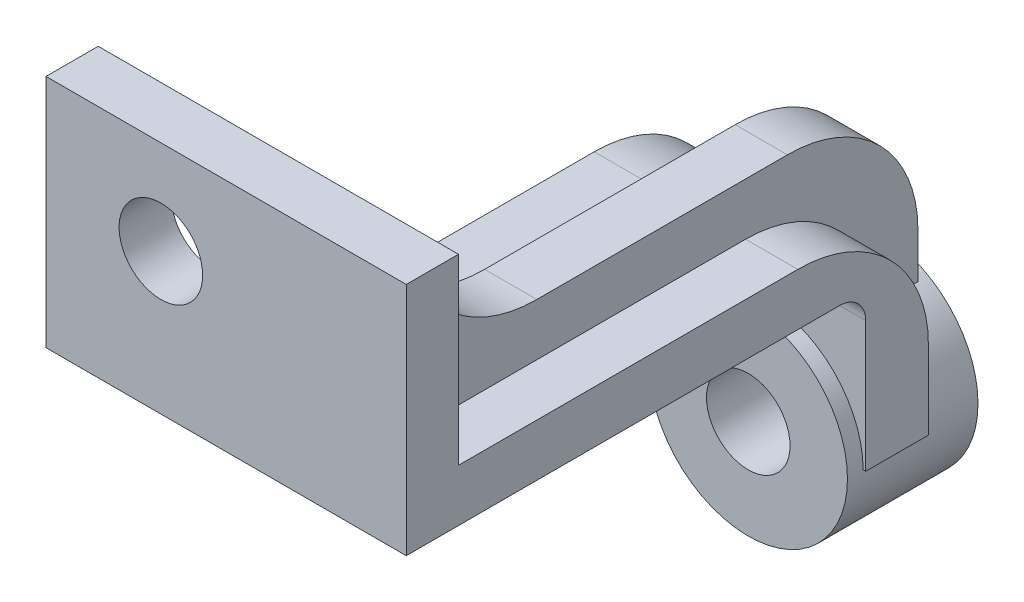
SolidWorks part; units mm, degrees
ref_plane "Ön Düzlem" through (0, 0, 0) normal (0, 0, 1) x (1, 0, 0)
ref_plane "Üst Düzlem" through (0, 0, 0) normal (0, 1, 0) x (1, 0, 0)
ref_plane "Sağ Düzlem" through (0, 0, 0) normal (1, 0, 0) x (0, 0, -1)
sketch "Çizim1" plane through (0, 0, 0) normal (0, 0, 1) x (1, 0, 0)
  line L1 (34.5, -22.5) -> (-34.5, -22.5)
  line L2 (34.5, -22.5) -> (34.5, 22.5)
  line L3 (34.5, 22.5) -> (-34.5, 22.5)
  line L4 (-34.5, -22.5) -> (-34.5, 22.5)
  line L5 (34.5, -22.5) -> (-34.5, 22.5) construction
  line L6 (34.5, 22.5) -> (-34.5, -22.5) construction
  circle A0 centre (-12.5, 4.5) radius 8
  point P0 (0, 0)
  point P8 (0, 0)
  point P10 (-8.0343, 5.2398)
  dimension "D3" = 22
  dimension "D4" = 18
  dimension "D1" = 45
  dimension "D2" = 69
extrude "Yükseklik-Ekstrüzyon1" add sketch "Çizim1" along normal blind 10
sketch "Çizim2" plane through (34.5, 0, 0) normal (1, 0, 0) x (0, 0, -1)
  line L0 (0, -12.5) -> (90, -12.5)
  line L1 (0, -22.5) -> (0, 22.5) construction
  line L2 (90, -12.5) -> (90, -52.5)
  line L3 (90, -52.5) -> (78, -52.5)
  line L4 (78, -52.5) -> (78, -22.5)
  line L5 (78, -22.5) -> (0, -22.5)
  line L6 (0, -12.5) -> (0, -22.5)
  dimension "D1" = 12
  dimension "D2" = 78
  dimension "D3" = 10
  dimension "D4" = 75
extrude "Yükseklik-Ekstrüzyon2" add sketch "Çizim2" against normal up to surface (69 mm away) up to face at (-34.5, 0, 5)
fillet "Radyus1" radius 5 1 edges at (0, -22.5, -78)
sketch "Çizim4" plane through (0, -12.5, 0) normal (0, 1, 0) x (1, 0, 0)
  line L0 (-34.5, 0) -> (-34.5, 90) construction
  line L1 (-4.5, 30) -> (-4.5, 90)
  line L2 (-34.5, 90) -> (34.5, 90) construction
  line L3 (-4.5, 90) -> (-34.5, 90)
  line L4 (-34.5, 90) -> (-62.3851, 41.0645)
  line L5 (-4.5, 90) -> (-34.5, 90)
  arc A0 (-58.2337, 48.3496) -> (-4.5, 30) centre (-34.5, 30) ccw
  line M1 (-34.5, 90) -> (-34.5, 0)
  line M4 (34.5, 90) -> (-34.5, 90)
extrude "Kes-Ekstrüzyon2" cut sketch "Çizim4" against normal blind 57 contours A0 L1 M1 M4 | L4 A0 M1
ref_plane "Düzlem2" through (24.5, 0, 0) normal (1, 0, 0) x (0, 0, -1)
sketch "Çizim6" plane through (0, 0, -90) normal (0, 0, -1) x (-1, 0, 0)
  line L0 (4.5, -52.5) -> (-34.5, -52.5) construction
  circle A0 centre (-15, -52.5) radius 19
extrude "Yükseklik-Ekstrüzyon3" add sketch "Çizim6" along normal blind 10
sketch "Çizim7" plane through (0, 0, -78) normal (0, 0, 1) x (1, 0, 0)
  line L0 (-4.5, -52.5) -> (34.5, -52.5) construction
  circle A0 centre (15, -52.5) radius 19
extrude "Yükseklik-Ekstrüzyon4" add sketch "Çizim7" along normal blind 3
loft "Loft1" add section face at (15, -62, -90) section face at (15, -62, -78)
ref_plane "Düzlem3" through (0, 0, -98) normal (0, 0, -1) x (-1, 0, 0)
sketch "Çizim15" plane through (24.5, 0, 0) normal (1, 0, 0) x (0, 0, -1)
  line L0 (0, 22.5) -> (0, -12.5)
  line L1 (0, -12.5) -> (90, -12.5)
  line L2 (90, -12.5) -> (90, -52.5)
  line L3 (90, -52.5) -> (98, -52.5)
  line L7 (25, -2.5) -> (98, -2.5)
  line L8 (98, -2.5) -> (98, -46.9373)
  line L9 (98, -46.9373) -> (98, -52.5)
  arc A0 (0, 22.5) -> (25, -2.5) centre (25, 22.5) ccw
  dimension "D2" = 10
extrude "Yükseklik-Ekstrüzyon5" add sketch "Çizim15" against normal blind 10
sketch "Çizim10" plane through (0, 0, -100) normal (0, 0, -1) x (-1, 0, 0)
  circle A0 centre (-15, -52.5) radius 8
extrude "Kes-Ekstrüzyon3" cut sketch "Çizim10" against normal up to next
fillet "Radyus3" radius 25 1 edges at (19.5, -2.5, -98)
fillet "Radyus4" radius 25 2 edges at (29.5, -12.5, -90) (5, -12.5, -90)
